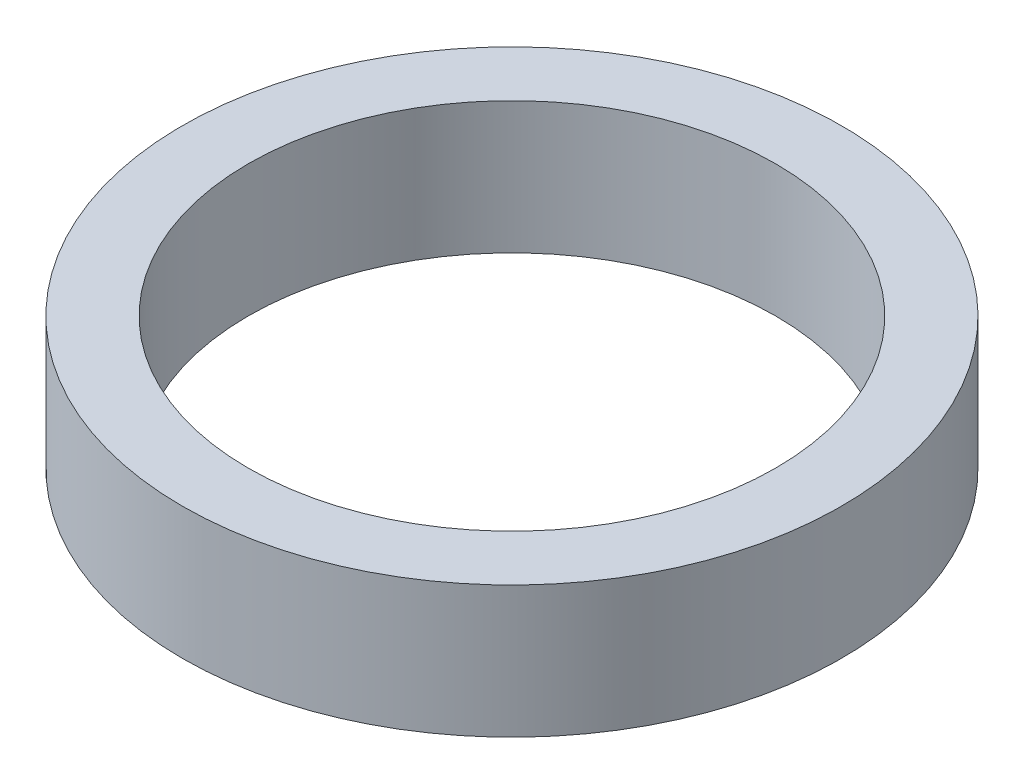
SolidWorks part; units mm, degrees
ref_plane "Front Plane" through (0, 0, 0) normal (0, 0, 1) x (1, 0, 0)
ref_plane "Top Plane" through (0, 0, 0) normal (0, 1, 0) x (1, 0, 0)
ref_plane "Right Plane" through (0, 0, 0) normal (1, 0, 0) x (0, 0, -1)
sketch "Sketch1" plane through (0, 0, 0) normal (1, 0, 0) x (0, 0, -1)
  line L0 (0, 174.4275) -> (0, -153.0534) construction
  line L1 (-250, 50) -> (-250, -50)
  line L2 (-250, -50) -> (-200, -50)
  line L3 (-200, -50) -> (-200, 50)
  line L4 (-200, 50) -> (-250, 50)
  line L5 (0, 0) -> (-144.1827, 0) construction
  point P9 (-200, 0)
  dimension "D1" = 100
  dimension "D2" = 500
  dimension "D3" = 400
revolve "Revolve1" add sketch "Sketch1" angle 360 about L0
